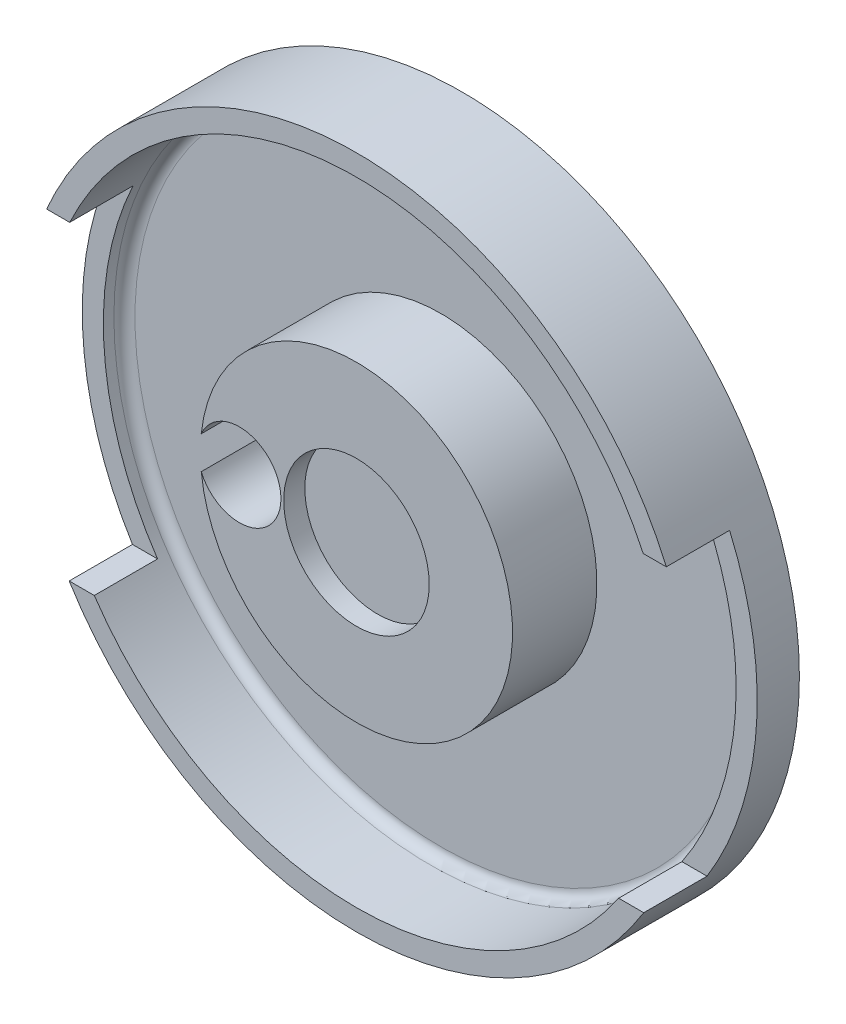
SolidWorks part; units mm, degrees
ref_plane "Front Plane" through (0, 0, 0) normal (0, 0, 1) x (1, 0, 0)
ref_plane "Top Plane" through (0, 0, 0) normal (0, 1, 0) x (1, 0, 0)
ref_plane "Right Plane" through (0, 0, 0) normal (1, 0, 0) x (0, 0, -1)
sketch "Sketch1" plane through (0, 0, 0) normal (0, 0, 1) x (1, 0, 0)
  circle A0 centre (0, 0) radius 16
extrude "Boss-Extrude1" add sketch "Sketch1" along normal blind 5
sketch "Sketch3" plane through (0, 0, 5) normal (0, 0, 1) x (1, 0, 0)
  circle A0 centre (0, 0) radius 15
extrude "Cut-Extrude1" cut sketch "Sketch3" against normal blind 4 contours A0
fillet "Fillet1" radius 0.5 1 edges at (15, 0, 1)
ref_plane "Plane4" through (0, 0, 13) normal (0, 0, 1) x (1, 0, 0)
sketch "Sketch7" plane through (0, 0, 13) normal (0, 0, 1) x (1, 0, 0)
  line L1 (-17.0905, 6.3393) -> (-11.822, 6.3393)
  line L2 (-17.0905, 6.3393) -> (-17.0905, -8.3958)
  line L3 (-17.0905, -8.3958) -> (-11.822, -8.3958)
  line L4 (-11.822, 6.3393) -> (-11.822, -8.3958)
  circle A0 centre (0, 0) radius 14.5 construction
extrude "Cut-Extrude2" cut sketch "Sketch7" against normal blind 11 contours L4 L3 L2 L1
mirror "Mirror1" about plane through (0, 0, 0) normal (1, 0, 0) of "Cut-Extrude2"
sketch "Sketch8" plane through (0, 0, 1) normal (0, 0, 1) x (1, 0, 0)
  circle A0 centre (0, 0) radius 7.4
extrude "Boss-Extrude2" add sketch "Sketch8" along normal blind 4 contours A0
sketch "Sketch9" plane through (0, 0, 5) normal (0, 0, 1) x (1, 0, 0)
  circle A0 centre (0, 0) radius 3.45
extrude "Cut-Extrude3" cut sketch "Sketch9" against normal blind 1
sketch "Sketch5" plane through (0, 0, 1) normal (0, 0, 1) x (1, 0, 0)
  circle A0 centre (0, 0) radius 1.275
  dimension "D1" = 2.55
sketch "Sketch6" plane through (0, 0, 13) normal (0, 0, 1) x (1, 0, 0)
  circle A0 centre (0, 0) radius 1.3
sketch "Sketch11" plane through (0, 0, 5) normal (0, 0, 1) x (1, 0, 0)
  circle A0 centre (-5.5497, 0) radius 1.9694
extrude "Cut-Extrude4" cut sketch "Sketch11" against normal blind 10
